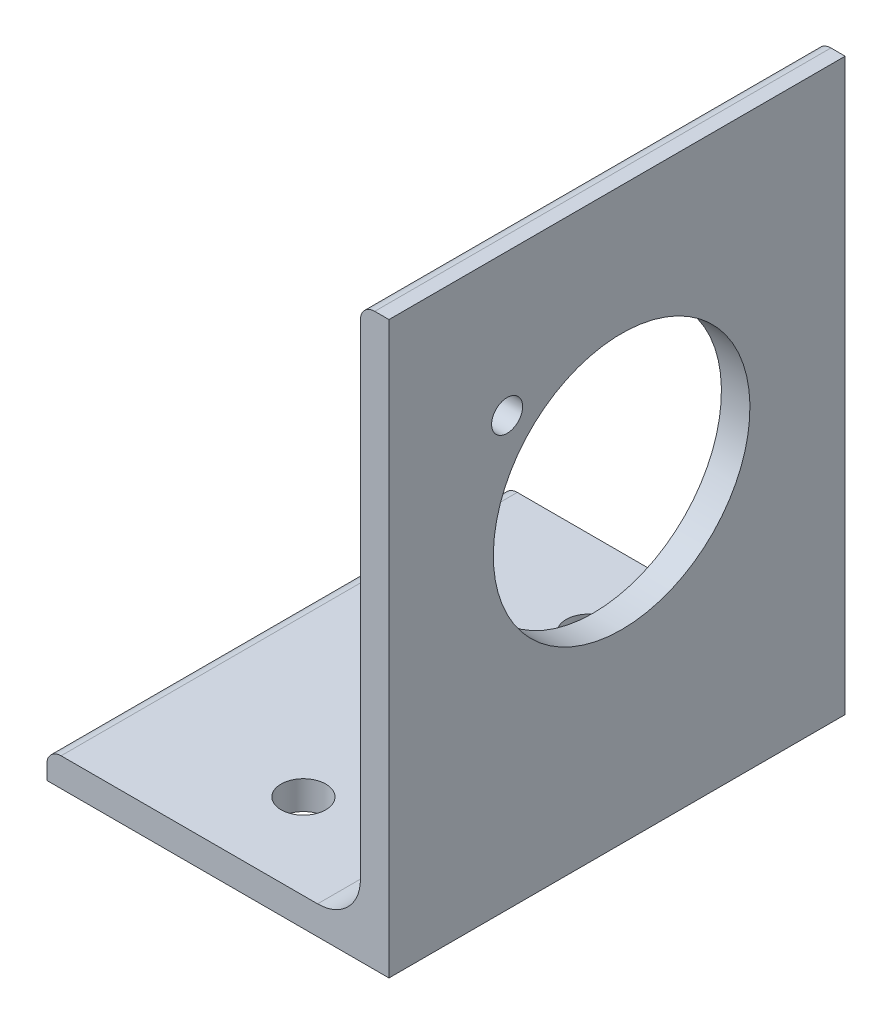
SolidWorks part; units mm, degrees
material "6061 Alloy"
ref_plane "Front Plane" through (0, 0, 0) normal (0, 0, 1) x (1, 0, 0)
ref_plane "Top Plane" through (0, 0, 0) normal (0, 1, 0) x (1, 0, 0)
ref_plane "Right Plane" through (0, 0, 0) normal (1, 0, 0) x (0, 0, -1)
sketch "Sketch0" plane through (0, 0, 0) normal (0, 0, 1) x (1, 0, 0)
  line L0 (-19.05, -31.75) -> (19.05, -31.75)
  line L1 (19.05, -31.75) -> (19.05, 31.75)
  line L2 (19.05, 0) -> (0, 0) construction
  line L3 (0, 0) -> (0, -31.75) construction
  line L4 (15.875, -23.7998) -> (15.875, 31.75) construction
  line L5 (11.0998, -28.575) -> (-19.05, -28.575) construction
  arc A0 (15.875, -23.7998) -> (11.0998, -28.575) centre (11.0998, -23.7998) cw
  point P3 (14.4764, -27.1764)
  dimension "Inside Corner Radius" = 4.7752
  dimension "Outside Height" = 63.5
  dimension "Inside Height" = 60.325
  dimension "Inside Width" = 34.925
  dimension "Wall Thickness" = 3.175
  dimension "D1" = 3.175
  dimension "Outside Width" = 38.1
sketch "Sketch1" plane through (0, 0, 0) normal (1, 0, 0) x (0, 0, -1)
  line L0 (25.4, 0) -> (-25.4, 0)
  point P4 (0, 0)
  dimension "Length" = 50.8
sketch "Sketch2" plane through (0, 0, 0) normal (0, 0, 1) x (1, 0, 0)
  line L0 (-19.05, -31.75) -> (19.05, -31.75)
  line L1 (19.05, -31.75) -> (19.05, 31.75)
  line L2 (19.05, 31.75) -> (15.875, 31.75) construction
  line L3 (15.875, 30.1625) -> (15.875, -23.7998)
  line L4 (11.0998, -28.575) -> (-17.4625, -28.575)
  line L5 (-19.05, -31.75) -> (-19.05, -28.575) construction
  line L6 (17.4625, 31.75) -> (19.05, 31.75)
  line L7 (-19.05, -30.1625) -> (-19.05, -31.75)
  line L8 (19.05, 0) -> (0, 0) construction
  line L9 (0, 0) -> (0, -31.75) construction
  arc A0 (15.875, 30.1625) -> (17.4625, 31.75) centre (17.4625, 30.1625) cw
  arc A1 (-19.05, -30.1625) -> (-17.4625, -28.575) centre (-17.4625, -30.1625) cw
  arc A2 (15.875, -23.7998) -> (11.0998, -28.575) centre (11.0998, -23.7998) cw
  dimension "Inside Radius" = 4.7752
  dimension "Height" = 63.5
  dimension "Width" = 38.1
  dimension "Thickness" = 3.175
extrude "Boss-Extrude1" add sketch "Sketch2" along normal mid plane 50.8
sketch "Break Locations" plane through (0, 0, 0) normal (1, 0, 0) x (0, 0, -1)
  line L0 (39.37, 0) -> (-39.37, 0)
  line L1 (-25.4, -31.75) -> (-25.4, 31.75) construction
  line L2 (25.4, -31.75) -> (25.4, 31.75) construction
  point P0 (28.575, 0)
  point P1 (-28.575, 0)
  point P10 (0, 0)
  point P11 (-39.37, 0)
  point P13 (39.37, 0)
  dimension "D1" = 53.975
  dimension "D2" = 53.975
  dimension "D3" = 64.77
sketch "Sketch3" plane through (15.875, 0, 0) normal (-1, 0, 0) x (0, 0, 1)
  line L0 (-0.508, 3.175) -> (12.244, 15.927) construction
  circle A0 centre (-0.508, 3.175) radius 14.2875
  circle A1 centre (12.244, 15.927) radius 1.7272
extrude "Cut-Extrude1" cut sketch "Sketch3" against normal through all
sketch "Sketch9" plane through (0, -31.75, 0) normal (0, -1, 0) x (1, 0, 0)
  line L0 (19.05, 0) -> (0, 0) construction
  line L1 (19.05, 25.4) -> (19.05, -25.4) construction
  line L2 (0, 0) -> (0, 15.875) construction
  line L3 (0, 0) -> (0, -15.875) construction
  circle A0 centre (0, 15.875) radius 2.4892
  circle A1 centre (0, -15.875) radius 2.4892
  dimension "D1" = 19.05
extrude "Cut-Extrude2" cut sketch "Sketch9" against normal through all
equation "\"D1@Break Locations\" = .85 * \"Height@Sketch2\""
equation "\"D2@Break Locations\"=\"D1@Break Locations\""
equation "\"Thickness@Sketch2\"=\"wall thickness@sketch0\""
equation "\"Height@Sketch2\"=\"outside height@sketch0\""
equation "\"Width@Sketch2\"=\"outside width@sketch0\""
equation "\"Inside Radius@Sketch2\"=\"inside corner radius@sketch0\""
equation "\"Length@Boss-Extrude1\"=\"length@sketch1\""
equation "\"D3@Break Locations\"=\"D2@Break Locations\"*1.2"
equation "\"D1@Sketch0\"=\"Wall Thickness@Sketch0\""
